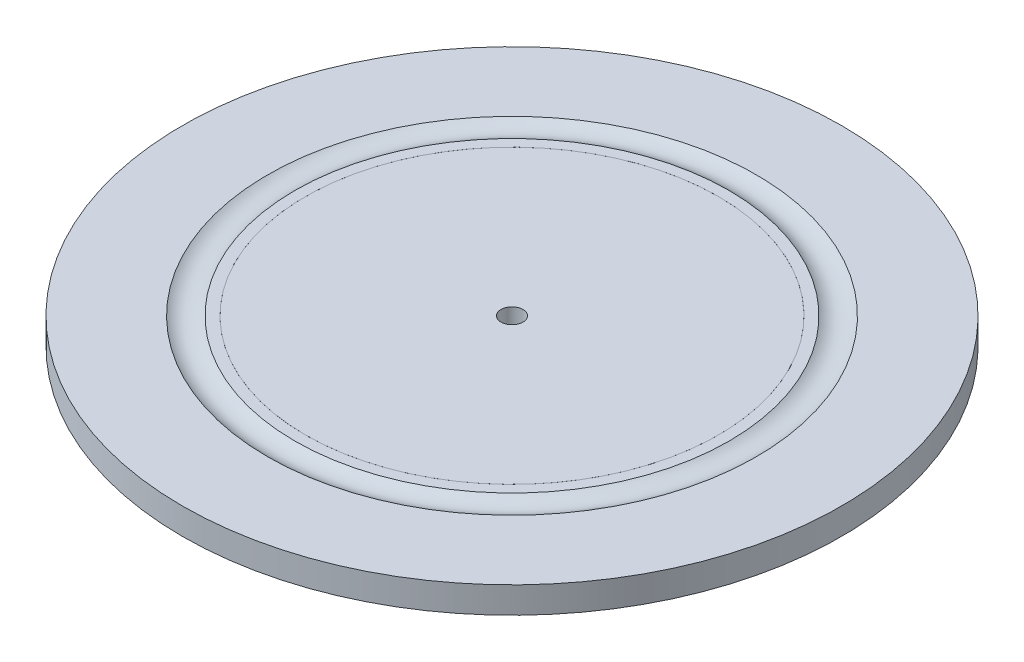
SolidWorks part; units mm, degrees
ref_plane "Front Plane" through (0, 0, 0) normal (0, 0, 1) x (1, 0, 0)
ref_plane "Top Plane" through (0, 0, 0) normal (0, 1, 0) x (1, 0, 0)
ref_plane "Right Plane" through (0, 0, 0) normal (1, 0, 0) x (0, 0, -1)
ref_plane "Plane1" through (0, 0, 0) normal (0, 0, -1) x (-1, 0, 0)
sketch "Sketch1" plane through (0, 0, 0) normal (0, 0, -1) x (-1, 0, 0)
  line L0 (-59, 0.8724) -> (-47, 0.8724)
  line L1 (-46, 1.8724) -> (-46, 5.8724)
  line L2 (-46, 5.8724) -> (-47, 6.8724)
  line L3 (-47, 6.8724) -> (-49.4043, 6.8724)
  line L4 (-55.5957, 6.8724) -> (-59, 6.8724)
  line L5 (-59, 6.8724) -> (-60, 5.8724)
  line L6 (-60, 5.8724) -> (-60, 1.8724)
  line L7 (0, 0) -> (0, 6.8724) construction
  arc A0 (-47, 0.8724) -> (-46, 1.8724) centre (-47, 1.8724) ccw
  arc A1 (-49.4043, 6.8724) -> (-55.5957, 6.8724) centre (-52.5, 11) cw
  arc A2 (-60, 1.8724) -> (-59, 0.8724) centre (-59, 1.8724) ccw
  dimension "D1" = 5.1595
  dimension "D2" = 14
  dimension "D3" = 6.1914
  dimension "D4" = 6
revolve "Revolve1" add sketch "Sketch1" angle 360 about L7
sketch "Sketch2" plane through (0, 0.8724, 0) normal (0, -1, 0) x (1, 0, 0)
  circle A0 centre (0, 0) radius 75
  circle A2 centre (0, 0) radius 46.9929
  circle A3 centre (0, 0) radius 59
extrude "Boss-Extrude1" add sketch "Sketch2" against normal blind 6 contours A0 A3 | A2
sketch "Sketch8" plane through (0, 6.8724, 0) normal (0, 1, 0) x (1, 0, 0)
  circle A0 centre (0, 0) radius 25
extrude "Cut-Extrude4" [suppressed] cut sketch "Sketch8" against normal blind 2
sketch "Sketch9" plane through (0, 6.8724, 0) normal (0, 1, 0) x (1, 0, 0)
  circle A0 centre (0, 0) radius 2.5
extrude "Cut-Extrude5" cut sketch "Sketch9" against normal blind 6
